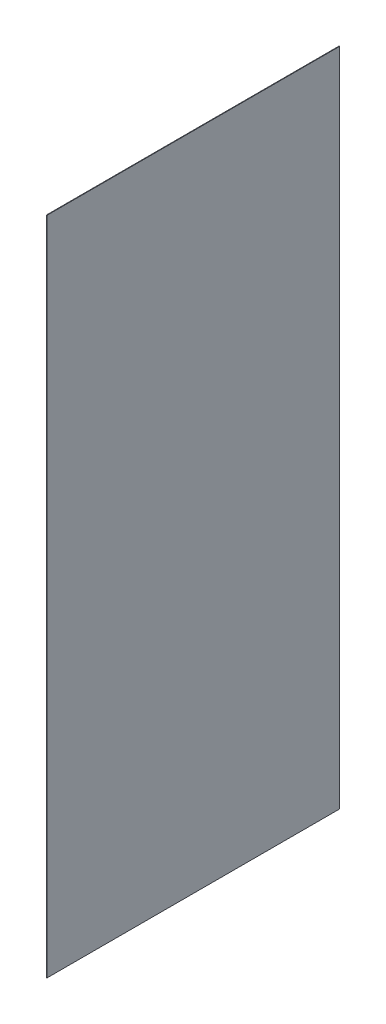
SolidWorks part; units mm, degrees
ref_plane "Front Plane" through (0, 0, 0) normal (0, 0, 1) x (1, 0, 0)
ref_plane "Top Plane" through (0, 0, 0) normal (0, 1, 0) x (1, 0, 0)
ref_plane "Right Plane" through (0, 0, 0) normal (1, 0, 0) x (0, 0, -1)
other "Configuration Table"
sketch "Sketch1" plane through (0, 0, 0) normal (0, 0, 1) x (1, 0, 0)
  line L1 (698.5, 120) -> (700, 120)
  line L2 (698.5, 120) -> (698.5, 1970)
  line L3 (698.5, 1970) -> (700, 1970)
  line L4 (700, 120) -> (700, 1970)
extrude "PRESS_dis_yan_sag_1" add sketch "Sketch1" against normal blind 820 separate body
